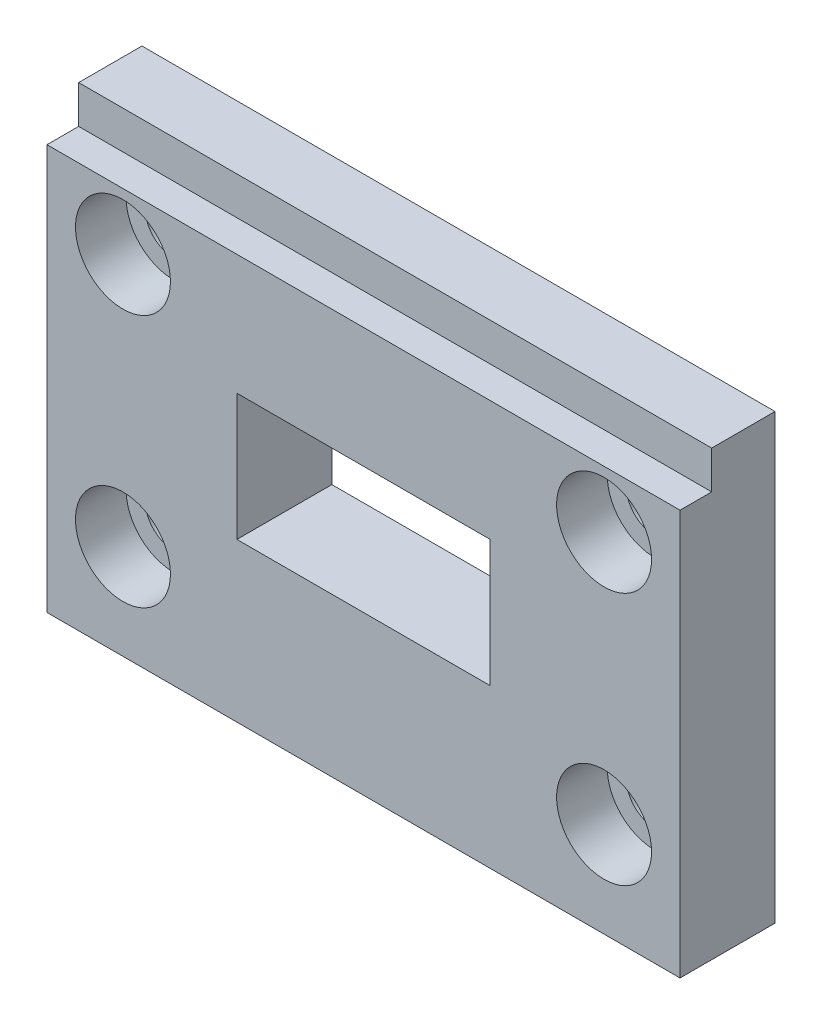
SolidWorks part; units mm, degrees
ref_plane "前视基准面" through (0, 0, 0) normal (0, 0, 1) x (1, 0, 0)
ref_plane "上视基准面" through (0, 0, 0) normal (0, 1, 0) x (1, 0, 0)
ref_plane "右视基准面" through (0, 0, 0) normal (1, 0, 0) x (0, 0, -1)
sketch "草图1" plane through (0, 0, 0) normal (0, 0, 1) x (1, 0, 0)
  line L0 (-50, -35) -> (50, -35)
  line L1 (50, -35) -> (50, 35)
  line L2 (50, 35) -> (-50, 35)
  line L3 (-50, 35) -> (-50, -35)
extrude "凸台-拉伸1" add sketch "草图1" along normal blind 15
ref_plane "基准面1" through (0, 0, 15) normal (0, 0, 1) x (1, 0, 0)
sketch "草图2" plane through (0, 0, 15) normal (0, 0, 1) x (1, 0, 0)
  line L0 (-50, 29) -> (50, 29)
  line L1 (50, 29) -> (50, 35)
  line L2 (50, 35) -> (-50, 35)
  line L3 (-50, 35) -> (-50, 29)
extrude "切除-拉伸1" cut sketch "草图2" against normal blind 5
sketch "草图3" plane through (0, 0, 0) normal (0, 0, 1) x (1, 0, 0)
  line L0 (-20, -10) -> (20, -10)
  line L1 (20, -10) -> (20, 10)
  line L2 (20, 10) -> (-20, 10)
  line L3 (-20, 10) -> (-20, -10)
extrude "切除-拉伸2" cut sketch "草图3" along normal through all
sketch "草图4" plane through (0, 0, 15) normal (0, 0, 1) x (1, 0, 0)
  circle A0 centre (38, 20) radius 7.5
  circle A1 centre (-38, 20) radius 7.5
  circle A2 centre (38, -20) radius 7.5
  circle A3 centre (-38, -20) radius 7.5
extrude "切除-拉伸3" cut sketch "草图4" against normal blind 8
sketch "草图5" plane through (0, 0, 15) normal (0, 0, 1) x (1, 0, 0)
  circle A0 centre (38, 20) radius 4.5
  circle A1 centre (-38, 20) radius 4.5
  circle A2 centre (38, -20) radius 4.5
  circle A3 centre (-38, -20) radius 4.5
extrude "切除-拉伸4" cut sketch "草图5" against normal through all
